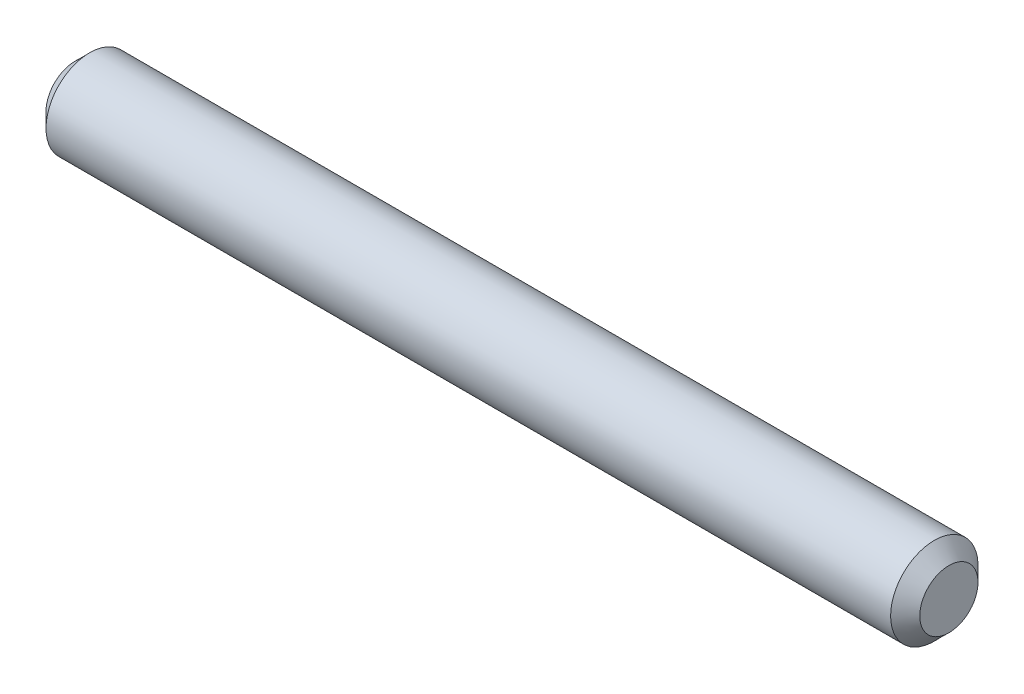
SolidWorks part; units mm, degrees
ref_plane "Front" through (0, 0, 0) normal (0, 0, 1) x (1, 0, 0)
ref_plane "Top" through (0, 0, 0) normal (0, 1, 0) x (1, 0, 0)
ref_plane "Right" through (0, 0, 0) normal (1, 0, 0) x (0, 0, -1)
sketch "Sketch1" plane through (0, 0, 0) normal (0, 0, 1) x (1, 0, 0)
  line L0 (0, 0) -> (33, 0) construction
  line L1 (1.5, 0) -> (1.5, 1)
  line L2 (1.5, 1) -> (2, 1.5)
  line L3 (2, 1.5) -> (31, 1.5)
  line L4 (31, 1.5) -> (31.5, 1)
  line L5 (31.5, 1) -> (31.5, 0)
  line L6 (31.5, 0) -> (1.5, 0)
  point P15 (16.5, 0)
  point P16 (16.5, 0)
  dimension "D1" = 0.5
  dimension "D2" = 30
  dimension "D3" = 0.5
  dimension "D4" = 1.5
  dimension "D5" = 33
revolve "Revolve1" add sketch "Sketch1" angle 360 about L0
